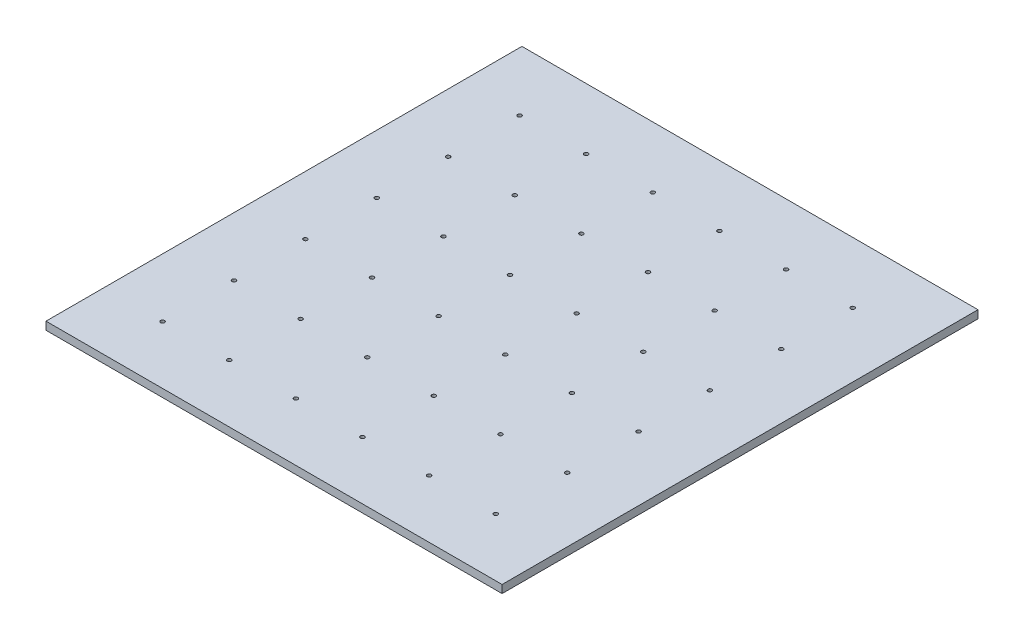
SolidWorks part; units mm, degrees
ref_plane "Front Plane" through (0, 0, 0) normal (0, 0, 1) x (1, 0, 0)
ref_plane "Top Plane" through (0, 0, 0) normal (0, 1, 0) x (1, 0, 0)
ref_plane "Right Plane" through (0, 0, 0) normal (1, 0, 0) x (0, 0, -1)
sketch "Sketch1" plane through (0, 0, 0) normal (0, 1, 0) x (1, 0, 0)
  line L1 (0, 0) -> (575, 0)
  line L2 (0, 0) -> (0, 600)
  line L3 (0, 600) -> (575, 600)
  line L4 (575, 0) -> (575, 600)
  dimension "D1" = 575
  dimension "D2" = 600
extrude "Boss-Extrude1" add sketch "Sketch1" along normal blind 10
sketch "Sketch2" plane through (0, 10, 0) normal (0, 1, 0) x (1, 0, 0)
  circle A0 centre (74, 73) radius 2.5
  circle A1 centre (158, 73) radius 2.5
  circle A2 centre (242, 73) radius 2.5
  circle A3 centre (326, 73) radius 2.5
  circle A4 centre (410, 73) radius 2.5
  circle A5 centre (494, 73) radius 2.5
  circle A6 centre (158, 163) radius 2.5
  circle A7 centre (242, 163) radius 2.5
  circle A8 centre (326, 163) radius 2.5
  circle A9 centre (410, 163) radius 2.5
  circle A10 centre (494, 163) radius 2.5
  circle A11 centre (158, 253) radius 2.5
  circle A12 centre (242, 253) radius 2.5
  circle A13 centre (326, 253) radius 2.5
  circle A14 centre (410, 253) radius 2.5
  circle A15 centre (494, 253) radius 2.5
  circle A16 centre (158, 343) radius 2.5
  circle A17 centre (242, 343) radius 2.5
  circle A18 centre (326, 343) radius 2.5
  circle A19 centre (410, 343) radius 2.5
  circle A20 centre (494, 343) radius 2.5
  circle A21 centre (158, 433) radius 2.5
  circle A22 centre (242, 433) radius 2.5
  circle A23 centre (326, 433) radius 2.5
  circle A24 centre (410, 433) radius 2.5
  circle A25 centre (494, 433) radius 2.5
  circle A26 centre (158, 523) radius 2.5
  circle A27 centre (242, 523) radius 2.5
  circle A28 centre (326, 523) radius 2.5
  circle A29 centre (410, 523) radius 2.5
  circle A30 centre (494, 523) radius 2.5
  circle A31 centre (74, 163) radius 2.5
  circle A32 centre (74, 253) radius 2.5
  circle A33 centre (74, 343) radius 2.5
  circle A34 centre (74, 433) radius 2.5
  circle A35 centre (74, 523) radius 2.5
  dimension "D3" = 5
  dimension "D1" = 73
  dimension "D2" = 74
  dimension "D4" = 6
  dimension "D5" = 6
extrude "Cut-Extrude1" cut sketch "Sketch2" against normal blind 10
